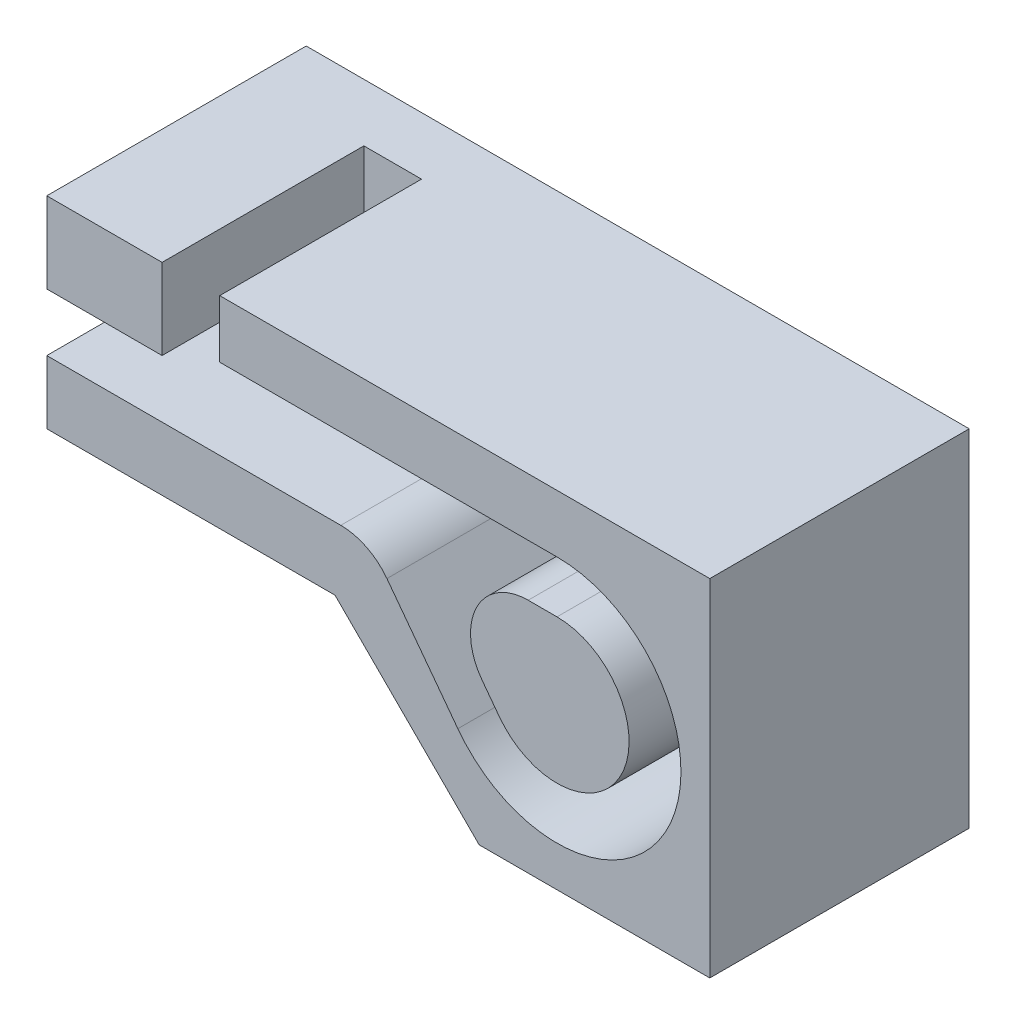
SolidWorks part; units mm, degrees
ref_plane "Plano frontal" through (0, 0, 0) normal (0, 0, 1) x (1, 0, 0)
ref_plane "Plano superior" through (0, 0, 0) normal (0, 1, 0) x (1, 0, 0)
ref_plane "Plano direito" through (0, 0, 0) normal (1, 0, 0) x (0, 0, -1)
sketch "Esboço1" plane through (0, 0, 0) normal (0, 0, 1) x (1, 0, 0)
  line L0 (-10, 0) -> (-10, 7)
  line L1 (-10, 7) -> (13, 7)
  line L2 (13, 7) -> (13, -5)
  line L3 (13, -5) -> (5, -5)
  line L4 (5, -5) -> (0, 0)
  line L5 (0, 0) -> (-10, 0)
  dimension "D1" = 7
  dimension "D2" = 10
  dimension "D3" = 5
  dimension "D4" = 5
  dimension "D5" = 8
extrude "Ressalto-extrusão1" add sketch "Esboço1" along normal blind 2
sketch "Esboço2" plane through (0, 0, 2) normal (0, 0, 1) x (1, 0, 0)
  line L0 (-4, 7) -> (-4, 5)
  line L1 (13, 7) -> (-10, 7) construction
  line L2 (6.7, 3.2) -> (7.7, 3.2)
  line L3 (5.1, 0) -> (5.7, -0.8)
  line L4 (-4, 7) -> (13, 7)
  line L5 (-4, 5) -> (7.7, 5)
  line L6 (1.8, 1.4) -> (4.26, -1.88)
  line L8 (13, 7) -> (13, -5)
  line L9 (-6, 7) -> (-6, 4.2)
  line L10 (-6, 4.2) -> (-10, 4.2)
  line L11 (-10, 7) -> (-10, 0) construction
  line L12 (-10, 4.2) -> (-10, 7)
  line L13 (-10, 7) -> (-6, 7)
  line L14 (0.2, 2.2) -> (-10, 2.2)
  line L15 (-10, 2.2) -> (-10, 0)
  arc A0 (6.7, 3.2) -> (5.1, 0) centre (6.7, 1.2) ccw
  arc A1 (5.7, -0.8) -> (7.7, 3.2) centre (7.7, 0.7) ccw
  arc A2 (4.26, -1.88) -> (7.7, 5) centre (7.7, 0.7) ccw
  arc A3 (1.8, 1.4) -> (0.2, 2.2) centre (0.2, 0.2) ccw
  line M11 (-10, 0) -> (0, 0)
  line M12 (0, 0) -> (5, -5)
  line M13 (5, -5) -> (13, -5)
  line M14 (13, -5) -> (13, 7)
  line M15 (13, 7) -> (-10, 7)
  line M16 (-10, 7) -> (-10, 0)
  dimension "D1" = 2
  dimension "D2" = 2.5
  dimension "D6" = 1
  dimension "D11" = 2
  dimension "D3" = 1
  dimension "D4" = 1.8
  dimension "D5" = 2
  dimension "D7" = 2
  dimension "D8" = 4
  dimension "D9" = 2.8
  dimension "D10" = 2
extrude "Ressalto-extrusão2" add sketch "Esboço2" along normal blind 7 contours L3 A1 L2 A0 | A2 L6 L14 L0 L5 M16 M11 M12 M13 M14 M15 | L10 L9 M15 M16
